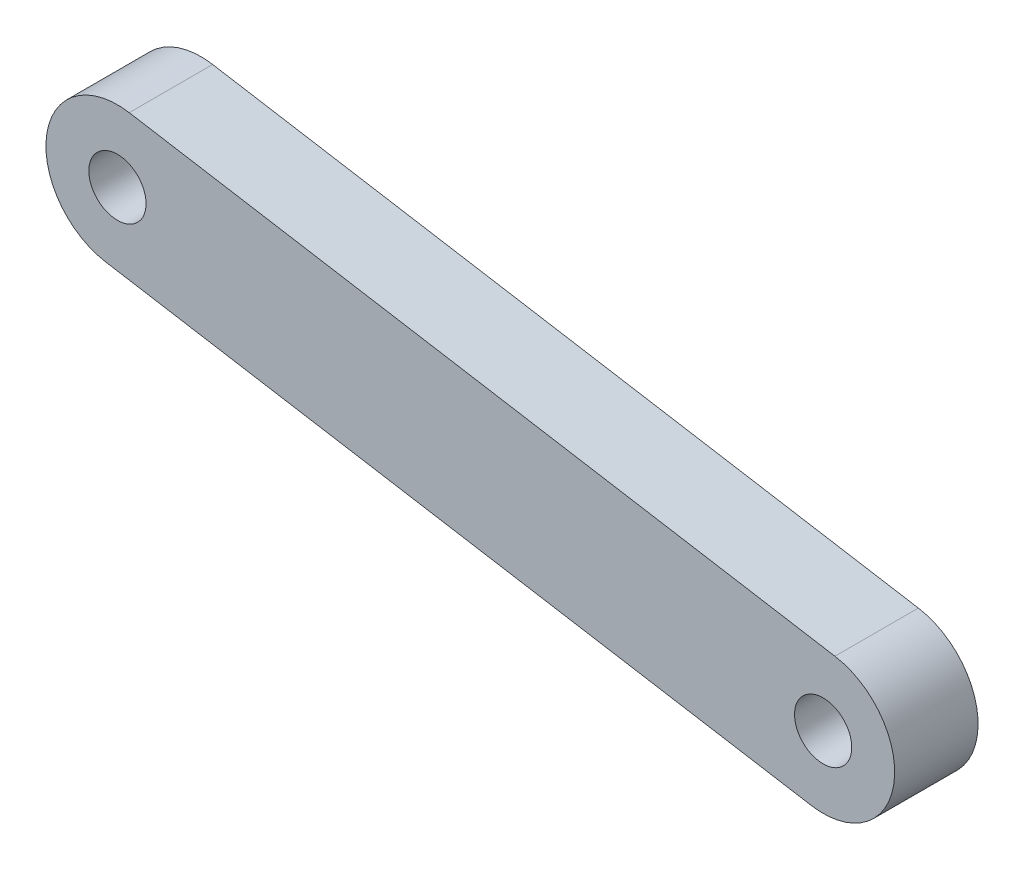
SolidWorks part; units mm, degrees
ref_plane "Front Plane" through (0, 0, 0) normal (0, 0, 1) x (1, 0, 0)
ref_plane "Top Plane" through (0, 0, 0) normal (0, 1, 0) x (1, 0, 0)
ref_plane "Right Plane" through (0, 0, 0) normal (1, 0, 0) x (0, 0, -1)
sketch "Sketch17" plane through (0, 0, 0) normal (0, 0, 1) x (1, 0, 0)
  line B0 (1718.6474, -653.3782) -> (4679.0427, -1148.0265)
  line B1 (1619.765, -1245.174) -> (4580.1604, -1739.8223)
  arc B2 (1718.6474, -653.3782) -> (1619.765, -1245.174) centre (1669.2062, -949.2761) ccw
  arc B3 (4580.1604, -1739.8223) -> (4679.0427, -1148.0265) centre (4629.6015, -1443.9244) ccw
  circle B4 centre (4629.6015, -1443.9244) radius 120
  circle B5 centre (1669.2062, -949.2761) radius 120
sketch_block_instance "Block13-1"
sketch_block "Block13"
extrude "Boss-Extrude12" add sketch "Sketch17" along normal blind 350 separate body
